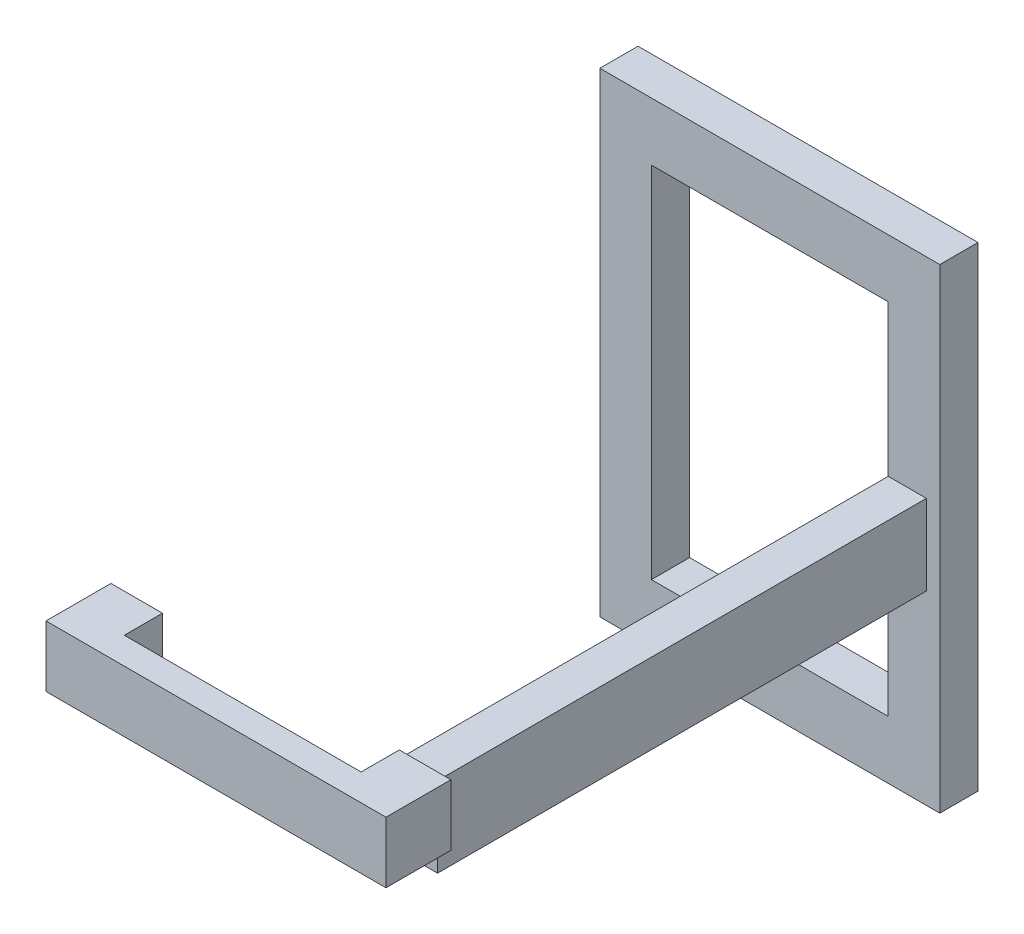
SolidWorks part; units mm, degrees
ref_plane "Front Plane" through (0, 0, 0) normal (0, 0, 1) x (1, 0, 0)
ref_plane "Top Plane" through (0, 0, 0) normal (0, 1, 0) x (1, 0, 0)
ref_plane "Right Plane" through (0, 0, 0) normal (1, 0, 0) x (0, 0, -1)
sketch "Sketch1" plane through (0, 0, 0) normal (0, 0, 1) x (1, 0, 0)
  line L1 (-30.9997, -46.998) -> (30.9997, -46.998)
  line L2 (-30.9997, -46.998) -> (-30.9997, 46.998)
  line L3 (-30.9997, 46.998) -> (30.9997, 46.998)
  line L4 (30.9997, -46.998) -> (30.9997, 46.998)
  line L5 (-30.9997, -46.998) -> (30.9997, 46.998) construction
  line L6 (-30.9997, 46.998) -> (30.9997, -46.998) construction
  line L7 (-44.5025, 62.1999) -> (44.5025, 62.1999)
  line L8 (-44.5025, 62.1999) -> (-44.5025, -62.1999)
  line L9 (-44.5025, -62.1999) -> (44.5025, -62.1999)
  line L10 (44.5025, 62.1999) -> (44.5025, -62.1999)
  line L11 (-44.5025, 62.1999) -> (44.5025, -62.1999) construction
  line L12 (-44.5025, -62.1999) -> (44.5025, 62.1999) construction
  point P0 (0, 0)
  point P6 (0, 0)
extrude "Boss-Extrude1" add sketch "Sketch1" along normal blind 10
sketch "Sketch2" plane through (0, 0, 10) normal (0, 0, 1) x (1, 0, 0)
  line L0 (30.9997, -46.998) -> (30.9997, 46.998) construction
  line L1 (30.9997, 7.4331) -> (40.9963, 7.4331)
  line L2 (30.9997, 7.4331) -> (30.9997, -13.5659)
  line L3 (30.9997, -13.5659) -> (40.9963, -13.5659)
  line L4 (40.9963, 7.4331) -> (40.9963, -13.5659)
extrude "Boss-Extrude2" add sketch "Sketch2" along normal blind 128
sketch "Sketch3" plane through (0, 0, 138) normal (0, 0, 1) x (1, 0, 0)
  line L1 (-30.9997, -46.998) -> (30.9997, -46.998)
  line L2 (-30.9997, -46.998) -> (-30.9997, 46.998)
  line L3 (-30.9997, 46.998) -> (30.9997, 46.998)
  line L4 (30.9997, -46.998) -> (30.9997, 46.998)
  line L5 (-30.9997, -46.998) -> (30.9997, 46.998) construction
  line L6 (-30.9997, 46.998) -> (30.9997, -46.998) construction
  line L7 (-44.5025, -62.1999) -> (44.5025, -62.1999)
  line L8 (-44.5025, -62.1999) -> (-44.5025, 62.1999)
  line L9 (-44.5025, 62.1999) -> (44.5025, 62.1999)
  line L10 (44.5025, -62.1999) -> (44.5025, 62.1999)
  line L11 (-44.5025, -62.1999) -> (44.5025, 62.1999) construction
  line L12 (-44.5025, 62.1999) -> (44.5025, -62.1999) construction
  point P0 (0, 0)
  point P7 (0, 0)
extrude "Boss-Extrude3" add sketch "Sketch3" along normal blind 17
sketch "Sketch4" plane through (0, 0, 155) normal (0, 0, 1) x (1, 0, 0)
  line L0 (-30.9997, 46.998) -> (-30.9997, -46.998) construction
  line L1 (-30.9997, 9.3935) -> (30.9997, 9.3935)
  line L2 (-30.9997, 9.3935) -> (-30.9997, -6.6163)
  line L3 (-30.9997, -6.6163) -> (30.9997, -6.6163)
  line L4 (30.9997, 9.3935) -> (30.9997, -6.6163)
  line L5 (30.9997, -46.998) -> (30.9997, 46.998) construction
extrude "Boss-Extrude4" add sketch "Sketch4" against normal blind 7
sketch "Sketch5" plane through (0, 0, 155) normal (0, 0, 1) x (1, 0, 0)
  line L5 (-44.5025, 62.1999) -> (-44.5025, -62.1999) construction
  line L6 (44.5025, -62.1999) -> (-44.5025, -62.1999)
  line L7 (44.5025, -62.1999) -> (44.5025, -6.6163)
  line L8 (44.5025, -6.6163) -> (-44.5025, -6.6163)
  line L9 (-44.5025, -62.1999) -> (-44.5025, -6.6163)
  line L10 (44.5025, -62.1999) -> (44.5025, 62.1999) construction
  line L11 (-44.5025, 62.1999) -> (44.5025, 62.1999)
  line L12 (-44.5025, 62.1999) -> (-44.5025, 9.3935)
  line L13 (-44.5025, 9.3935) -> (44.5025, 9.3935)
  line L14 (44.5025, 62.1999) -> (44.5025, 9.3935)
extrude "Cut-Extrude1" cut sketch "Sketch5" against normal blind 17
